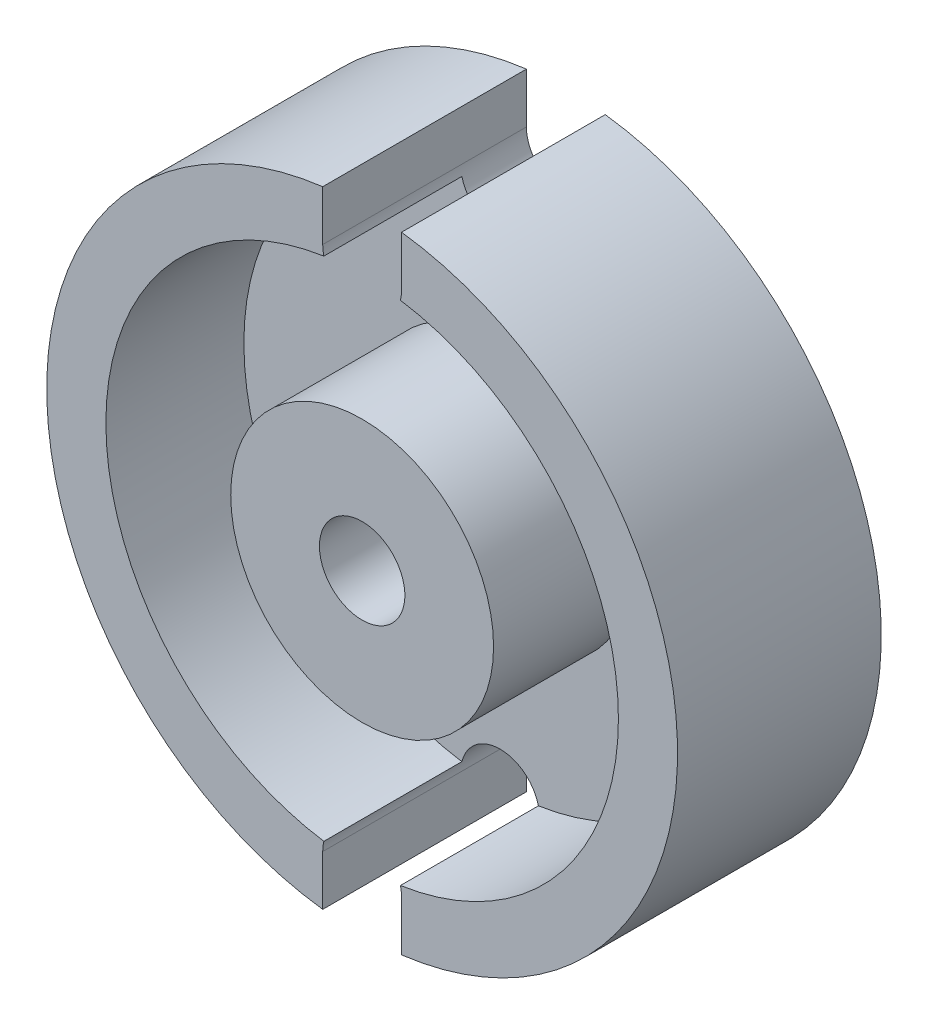
SolidWorks part; units mm, degrees
ref_plane "Спереди" through (0, 0, 0) normal (0, 0, 1) x (1, 0, 0)
ref_plane "Сверху" through (0, 0, 0) normal (0, 1, 0) x (1, 0, 0)
ref_plane "Справа" through (0, 0, 0) normal (1, 0, 0) x (0, 0, -1)
sketch "Эскиз1" plane through (0, 0, 0) normal (0, 0, 1) x (1, 0, 0)
  circle A0 centre (0, 0) radius 24
  circle A1 centre (0, 0) radius 3.25
  dimension "D1" = 48
  dimension "D2" = 6.5
extrude "Вытянуть1" add sketch "Эскиз1" along normal blind 15.5
sketch "Эскиз2" plane through (0, 0, 15.5) normal (0, 0, 1) x (1, 0, 0)
  circle A0 centre (0, 0) radius 19.5
  circle A1 centre (0, 0) radius 10
  dimension "D1" = 39
  dimension "D2" = 20
extrude "Вырез-Вытянуть1" cut sketch "Эскиз2" against normal blind 10.5
sketch "Эскиз3" plane through (0, 0, 0) normal (0, 0, -1) x (-1, 0, 0)
  line L0 (0, 26.8727) -> (0, -27.6578) construction
  line L1 (-12.5977, 0) -> (11.1702, 0) construction
  line L2 (3, 20) -> (3, 23.8118)
  line L3 (-3, 20) -> (-3, 23.8118)
  line L4 (3, -20) -> (3, -23.8118)
  line L5 (-3, -20) -> (-3, -23.8118)
  arc A0 (3, -20) -> (-3, -20) centre (0, -20) ccw
  arc A1 (-3, 20) -> (3, 20) centre (0, 20) ccw
  circle A2 centre (0, 0) radius 24 construction
  arc A3 (-3, -23.8118) -> (3, -23.8118) centre (0, 0) ccw
  arc A4 (3, 23.8118) -> (-3, 23.8118) centre (0, 0) ccw
  dimension "D1" = 40
  dimension "D2" = 6
extrude "Вырез-Вытянуть2" cut sketch "Эскиз3" against normal blind 20
